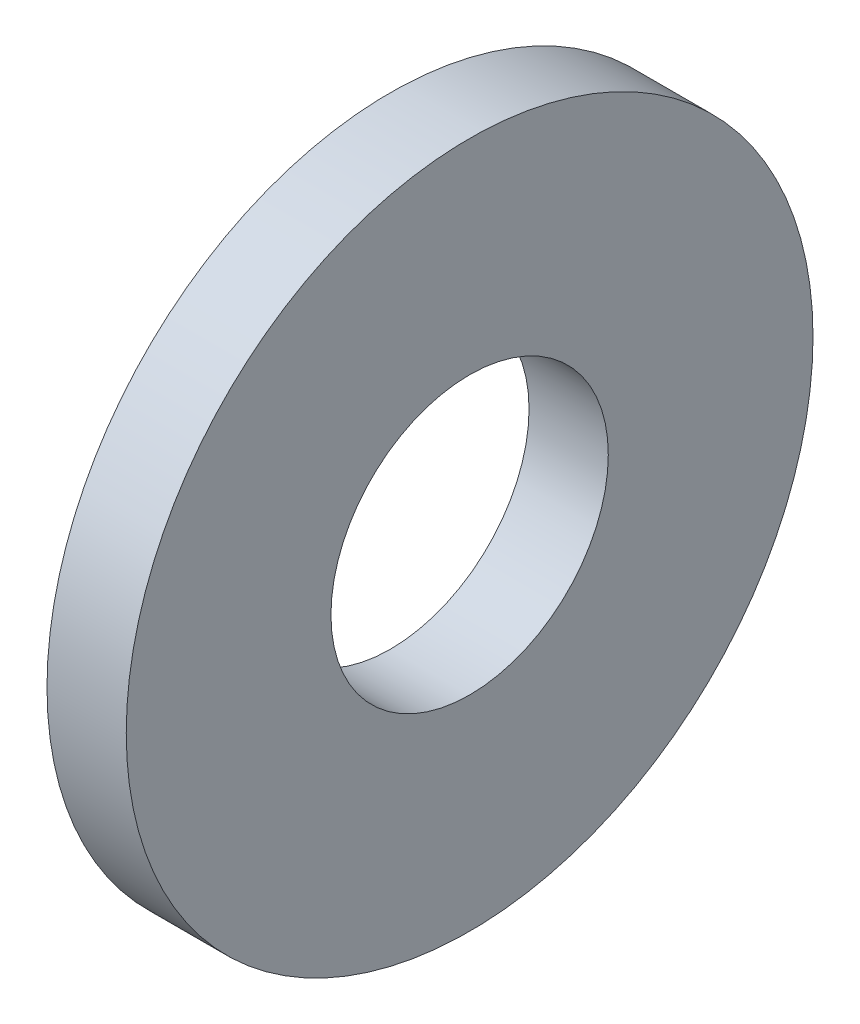
SolidWorks part; units mm, degrees
ref_plane "前视基准面" through (0, 0, 0) normal (0, 0, 1) x (1, 0, 0)
ref_plane "上视基准面" through (0, 0, 0) normal (0, 1, 0) x (1, 0, 0)
ref_plane "右视基准面" through (0, 0, 0) normal (1, 0, 0) x (0, 0, -1)
sketch "草图1" plane through (0, 0, 0) normal (1, 0, 0) x (0, 0, -1)
  circle A0 centre (0, 0) radius 13
  circle A1 centre (0, 0) radius 5.25
  dimension "D1" = 26
  dimension "D2" = 10.5
extrude "凸台-拉伸1" add sketch "草图1" along normal blind 3
